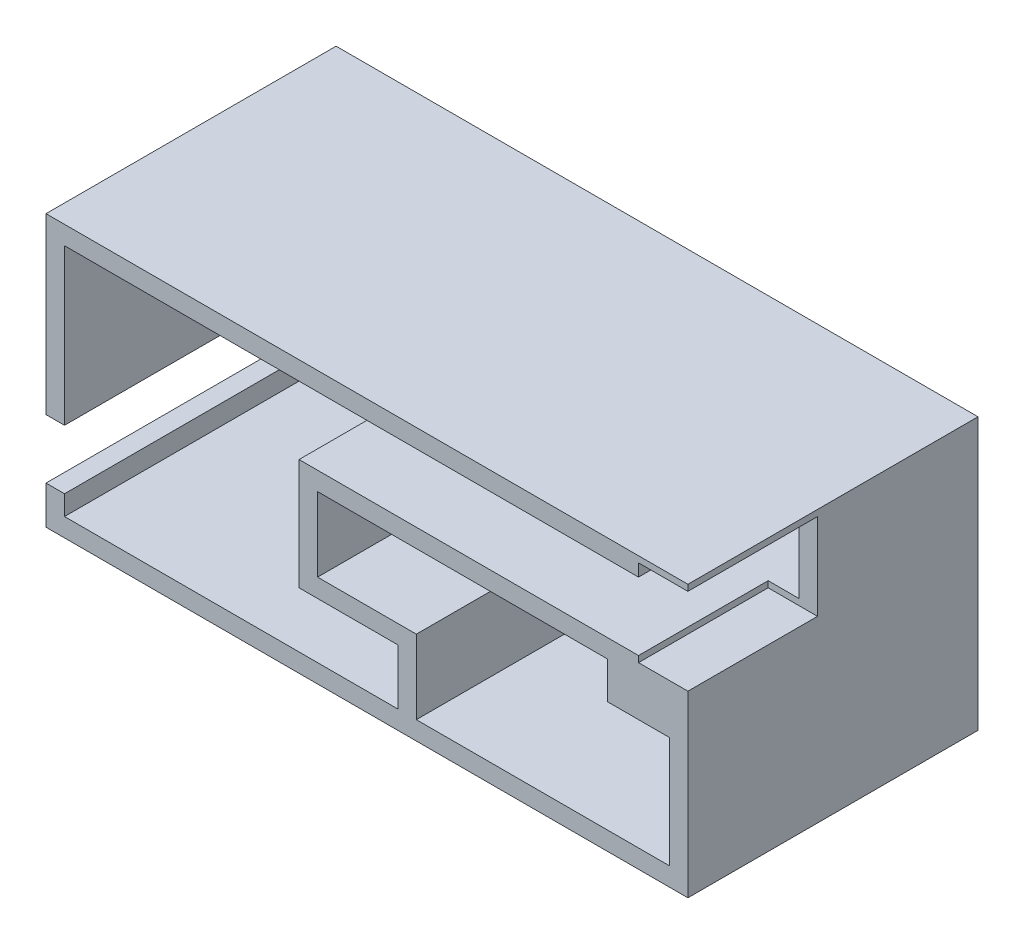
SolidWorks part; units mm, degrees
ref_plane "Front Plane" through (0, 0, 0) normal (0, 0, 1) x (1, 0, 0)
ref_plane "Top Plane" through (0, 0, 0) normal (0, 1, 0) x (1, 0, 0)
ref_plane "Right Plane" through (0, 0, 0) normal (1, 0, 0) x (0, 0, -1)
sketch "Sketch1" plane through (0, 0, 0) normal (0, 0, 1) x (1, 0, 0)
  line L0 (-44.6807, 0) -> (45.937, 0) construction
  line L2 (-19.2815, 0) -> (32.7185, 0)
  line L3 (-19.2815, 0) -> (-19.2815, 22)
  line L4 (-19.2815, 22) -> (32.7185, 22)
  line L5 (32.7185, 0) -> (32.7185, 22)
  dimension "D1" = 52
  dimension "D2" = 22
extrude "Boss-Extrude1" add sketch "Sketch1" along normal blind 1.5
sketch "Sketch2" plane through (0, 0, 1.5) normal (0, 0, 1) x (1, 0, 0)
  line L4 (-17.7815, 20.5) -> (-17.7815, 1.5)
  line L5 (-17.7815, 1.5) -> (9.2185, 1.5)
  line L6 (31.2185, 1.5) -> (31.2185, 10.5)
  line L7 (31.2185, 20.5) -> (-17.7815, 20.5)
  line L8 (-19.2815, 22) -> (-19.2815, 0)
  line L9 (-19.2815, 0) -> (32.7185, 0)
  line L10 (32.7185, 0) -> (32.7185, 22)
  line L11 (32.7185, 22) -> (-19.2815, 22)
  line L12 (-19.2815, 22) -> (-19.2815, 0)
  line L13 (-19.2815, 0) -> (32.7185, 0)
  line L14 (32.7185, 0) -> (32.7185, 22)
  line L15 (32.7185, 22) -> (-19.2815, 22)
  line L16 (-17.7815, 6) -> (9.2185, 6) construction
  line L17 (-17.7815, 15) -> (31.2185, 15) construction
  line L18 (31.2185, 15) -> (1.2185, 15)
  line L19 (1.2185, 15) -> (1.2185, 6)
  line L20 (1.2185, 6) -> (9.2185, 6)
  line L21 (9.2185, 6) -> (9.2185, 1.5)
  line L22 (26.2185, 13.5) -> (2.7185, 13.5)
  line L23 (2.7185, 13.5) -> (2.7185, 7.5)
  line L24 (2.7185, 7.5) -> (10.7185, 7.5)
  line L25 (10.7185, 7.5) -> (10.7185, 1.5)
  line L26 (31.2185, 15) -> (31.2185, 20.5)
  line L27 (31.2185, 1.5) -> (31.2185, 20.5) construction
  line L28 (10.7185, 1.5) -> (31.2185, 1.5)
  line L29 (-17.7815, 1.5) -> (31.2185, 1.5) construction
  line L30 (26.2185, 13.5) -> (26.2185, 10.5)
  line L31 (26.2185, 10.5) -> (31.2185, 10.5)
  line L32 (31.2185, 13.5) -> (2.7185, 13.5) construction
  dimension "D3" = 4.5
  dimension "D4" = 5.5
  dimension "D5" = 30
  dimension "D6" = 27
  dimension "D8" = 3
  dimension "D9" = 5
  dimension "D1" = 0
  dimension "D2" = 1.5
  dimension "D7" = 1.5
extrude "Boss-Extrude2" add sketch "Sketch2" along normal blind 22
sketch "Sketch3" plane through (-19.2815, 0, 0) normal (-1, 0, 0) x (0, 0, 1)
  line L0 (0, 5.5) -> (23.5, 5.5) construction
  line L1 (0, 22) -> (0, 0) construction
  line L2 (23.5, 22) -> (23.5, 0) construction
  line L3 (23.5, 0) -> (0, 0) construction
  line L4 (5.75, 3.1) -> (17.75, 3.1)
  line L5 (5.75, 3.1) -> (5.75, 7.9)
  line L6 (5.75, 7.9) -> (17.75, 7.9)
  line L8 (5.75, 3.1) -> (17.75, 7.9) construction
  line L9 (5.75, 7.9) -> (17.75, 3.1) construction
  line L10 (17.75, 7.9) -> (23.5, 7.9)
  line L11 (17.75, 3.1) -> (23.5, 3.1)
  line L12 (23.5, 7.9) -> (23.5, 3.1)
  point P6 (11.75, 5.5)
  dimension "D1" = 4.8
  dimension "D2" = 12
  dimension "D3" = 5.5
extrude "Cut-Extrude1" cut sketch "Sketch3" against normal blind 5
sketch "Sketch6" plane through (32.7185, 0, 0) normal (1, 0, 0) x (0, 0, -1)
  line L0 (-23.5, 18) -> (0, 18) construction
  line L1 (-23.5, 0) -> (-23.5, 22) construction
  line L2 (0, 0) -> (0, 22) construction
  line L3 (-23.5, 22) -> (0, 22) construction
  line L7 (-23.5, 21.5) -> (-13, 21.5)
  line L8 (-13, 21.5) -> (-13, 14.5)
  line L9 (-13, 14.5) -> (-23.5, 14.5)
  line L10 (-23.5, 21.5) -> (-23.5, 14.5)
  dimension "D1" = 7
  dimension "D2" = 4
  dimension "D3" = 3.5
  dimension "D4" = 13
extrude "Cut-Extrude2" cut sketch "Sketch6" against normal blind 4
